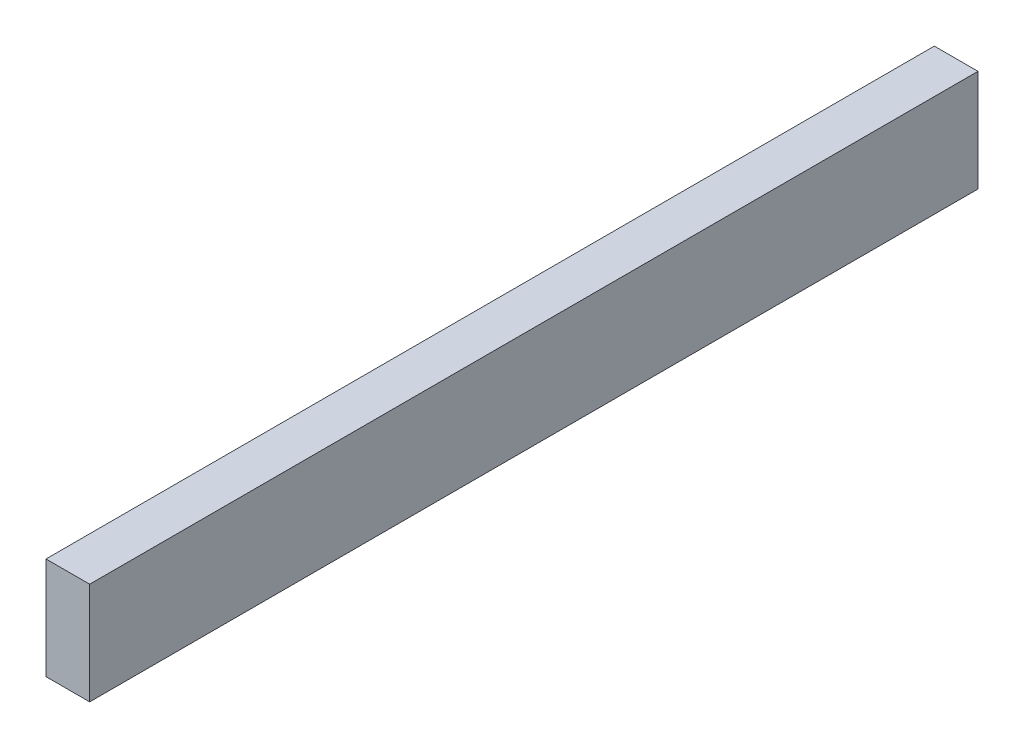
SolidWorks part; units mm, degrees
material "Pine"
ref_plane "Front Plane" through (0, 0, 0) normal (0, 0, 1) x (1, 0, 0)
ref_plane "Top Plane" through (0, 0, 0) normal (0, 1, 0) x (1, 0, 0)
ref_plane "Right Plane" through (0, 0, 0) normal (1, 0, 0) x (0, 0, -1)
sketch "Sketch1" plane through (0, 0, 0) normal (0, 0, 1) x (1, 0, 0)
  line L1 (-477.3033, -432.2831) -> (-439.2033, -432.2831)
  line L2 (-477.3033, -432.2831) -> (-477.3033, -521.1831)
  line L3 (-477.3033, -521.1831) -> (-439.2033, -521.1831)
  line L4 (-439.2033, -432.2831) -> (-439.2033, -521.1831)
extrude "Boss-Extrude1" add sketch "Sketch1" along normal blind 774.7
